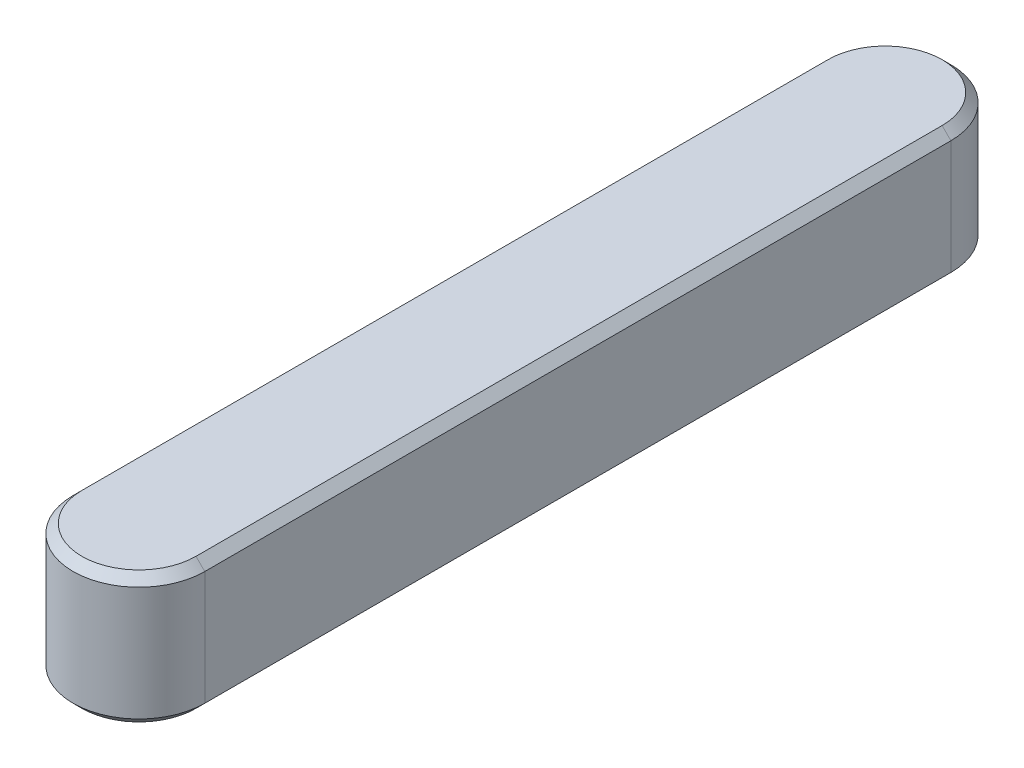
SolidWorks part; units mm, degrees
ref_plane "Front Plane" through (0, 0, 0) normal (0, 0, 1) x (1, 0, 0)
ref_plane "Top Plane" through (0, 0, 0) normal (0, 1, 0) x (1, 0, 0)
ref_plane "Right Plane" through (0, 0, 0) normal (1, 0, 0) x (0, 0, -1)
sketch "Sketch1" plane through (0, 0, 0) normal (0, 0, 1) x (1, 0, 0)
  line L0 (-24.8891, 14.0503) -> (-24.8891, 11.0503)
  line L1 (-24.8891, 14.0503) -> (-21.8891, 14.0503)
  line L2 (-21.8891, 14.0503) -> (-21.8891, 11.0503)
  line L3 (-21.8891, 11.0503) -> (-24.8891, 11.0503)
  dimension "D1" = 3
  dimension "D2" = 3
extrude "Extrude1" add sketch "Sketch1" along normal blind 20
sketch "Sketch2" plane through (0, 14.0503, 0) normal (0, 1, 0) x (1, 0, 0)
  line L4 (-21.8891, 0) -> (-24.8891, 0)
  line L5 (-24.8891, 0) -> (-24.8891, -20)
  line L6 (-24.8891, -20) -> (-21.8891, -20)
  line L7 (-21.8891, -20) -> (-21.8891, 0)
  line L9 (-24.8891, -1.5) -> (-24.8891, -18.5)
  line L11 (-21.8891, -18.5) -> (-21.8891, -1.5)
  arc A0 (-21.8891, -1.5) -> (-24.8891, -1.5) centre (-23.3891, -1.5) ccw
  arc A1 (-24.8891, -18.5) -> (-21.8891, -18.5) centre (-23.3891, -18.5) ccw
  dimension "D3" = 1.5
  dimension "D2" = 1.5
  dimension "D1" = 0
extrude "Cut-Extrude1" cut sketch "Sketch2" against normal blind 20 flip side to cut
chamfer "Chamfer1" distance 0.2 angle 45 8 edges at (-23.3891, 11.0503, 0) (-24.8891, 11.0503, 10) (-21.8891, 11.0503, 10) (-23.3891, 11.0503, 20) (-23.3891, 14.0503, 0) (-24.8891, 14.0503, 10) (-21.8891, 14.0503, 10) (-23.3891, 14.0503, 20)
